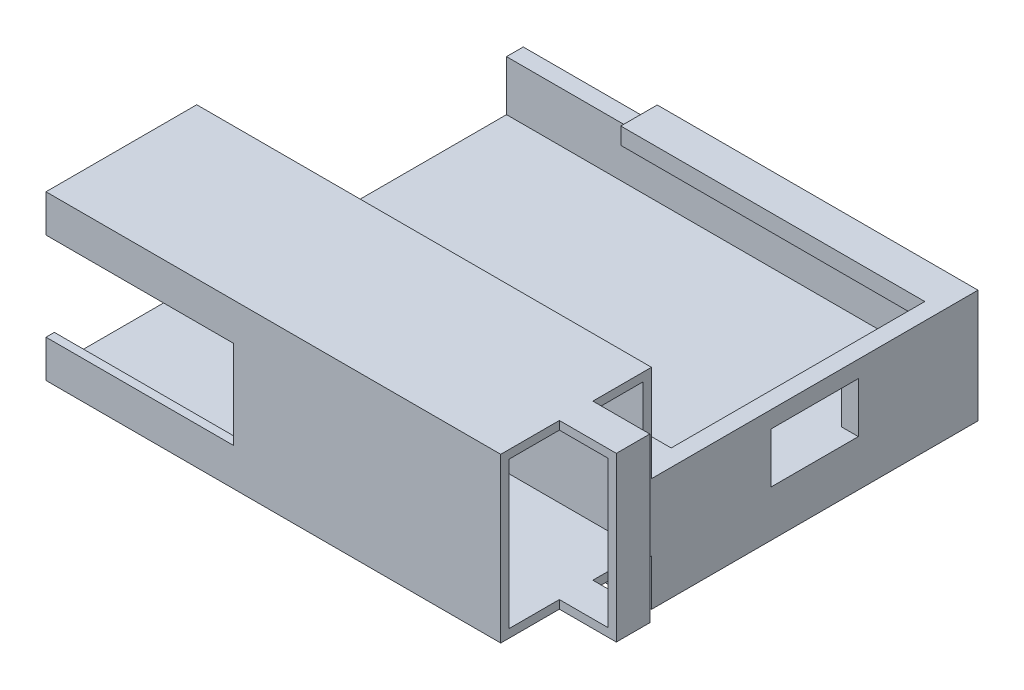
SolidWorks part; units mm, degrees
ref_plane "Front Plane" through (0, 0, 0) normal (0, 0, 1) x (1, 0, 0)
ref_plane "Top Plane" through (0, 0, 0) normal (0, 1, 0) x (1, 0, 0)
ref_plane "Right Plane" through (0, 0, 0) normal (1, 0, 0) x (0, 0, -1)
sketch "Sketch1" plane through (0, 0, 0) normal (1, 0, 0) x (0, 0, -1)
  line L0 (-3.4975, 0) -> (3.9817, 0) construction
  line L1 (-27.7749, 9.525) -> (-24.0411, 9.525)
  line L2 (0, 6.3447) -> (0, -3.1803) construction
  line L7 (-27.7749, 0) -> (27.7749, 0)
  line L8 (-27.7749, 0) -> (-27.7749, 9.525)
  line L9 (27.7749, 0) -> (27.7749, 9.525)
  line L10 (27.7749, 9.525) -> (24.0411, 9.525)
  line L11 (30.9499, 12.7) -> (24.0411, 12.7)
  line L12 (30.9499, -3.175) -> (30.9499, 12.7)
  line L14 (-30.9499, -3.175) -> (-30.9499, 12.7)
  line L15 (-30.9499, 12.7) -> (-24.0411, 12.7)
  line L16 (-24.0411, 12.7) -> (-24.0411, 9.525)
  line L17 (24.0411, 12.7) -> (24.0411, 9.525)
  line L18 (-30.9499, -8.763) -> (30.9499, -8.763)
  line L19 (-30.9499, -3.175) -> (-30.9499, -8.763)
  line L20 (30.9499, -3.175) -> (30.9499, -8.763)
  line L22 (-30.9499, -3.175) -> (30.9499, -3.175) construction
  point P3 (0, 0)
  dimension "D1" = 3.7338
  dimension "D2" = 3.175
  dimension "D4" = 9.525
extrude "Boss-Extrude1" add sketch "Sketch1" along normal blind 83.0326
sketch "Sketch2" plane through (83.0326, 0, 0) normal (1, 0, 0) x (0, 0, -1)
  line L0 (-30.9499, 12.7) -> (30.9499, 12.7)
  line L1 (30.9499, 12.7) -> (30.9499, -8.763)
  line L2 (30.9499, -8.763) -> (-30.9499, -8.763)
  line L3 (-30.9499, -8.763) -> (-30.9499, 12.7)
extrude "Boss-Extrude2" add sketch "Sketch2" along normal blind 3.175
sketch "Sketch3" plane through (0, 0, 30.9499) normal (0, 0, 1) x (1, 0, 0)
  line L0 (0, -4.8159) -> (86.2076, -4.8159) construction
  line L1 (0, 12.7) -> (0, -8.763) construction
  line L2 (86.2076, 12.7) -> (86.2076, -8.763) construction
  line L3 (43.1038, 12.7) -> (43.1038, -8.763) construction
  line L4 (36.7538, -7.3559) -> (11.3538, -7.3559)
  line L5 (36.7538, -7.3559) -> (36.7538, -2.2759)
  line L6 (36.7538, -2.2759) -> (11.3538, -2.2759)
  line L7 (11.3538, -7.3559) -> (11.3538, -2.2759)
  line L8 (36.7538, -7.3559) -> (11.3538, -2.2759) construction
  line L9 (36.7538, -2.2759) -> (11.3538, -7.3559) construction
  line L10 (86.2076, 12.7) -> (0, 12.7) construction
  line L11 (86.2076, -8.763) -> (0, -8.763) construction
  line L12 (74.8538, -7.3559) -> (74.8538, -2.2759)
  line L13 (49.4538, -2.2759) -> (74.8538, -2.2759)
  line L14 (49.4538, -7.3559) -> (49.4538, -2.2759)
  line L15 (49.4538, -7.3559) -> (74.8538, -7.3559)
  line L16 (24.0538, -2.2759) -> (24.0538, -7.3559) construction
  point P6 (24.0538, -4.8159)
  dimension "D1" = 25.4
  dimension "D2" = 19.05
  dimension "D3" = 5.08
extrude "Cut-Extrude1" cut sketch "Sketch3" against normal through all
fillet "Fillet1" radius 0.762 4 edges at (62.1538, -7.3559, -30.9499) (24.0538, -7.3559, -30.9499) (62.1538, -7.3559, 30.9499) (24.0538, -7.3559, 30.9499)
fillet "Fillet2" radius 0.762 6 edges at (11.3538, -5.1969, -30.9499) (24.0538, -2.2759, -30.9499) (36.7538, -5.1969, -30.9499) (49.4538, -5.1969, -30.9499) (62.1538, -2.2759, -30.9499) (74.8538, -5.1969, -30.9499)
fillet "Fillet3" radius 0.762 6 edges at (74.8538, -5.1969, 30.9499) (62.1538, -2.2759, 30.9499) (49.4538, -5.1969, 30.9499) (11.3538, -5.1969, 30.9499) (24.0538, -2.2759, 30.9499) (36.7538, -5.1969, 30.9499)
sketch "Sketch5" plane through (83.0326, 0, 0) normal (-1, 0, 0) x (0, 0, 1)
  line L0 (-27.7749, 4.7625) -> (27.7749, 4.7625) construction
  line L1 (-27.7749, 9.525) -> (-27.7749, 0) construction
  line L2 (27.7749, 0) -> (27.7749, 9.525) construction
  line L4 (8.265, 0) -> (-8.265, 0)
  line L5 (8.265, 0) -> (8.265, 9.525)
  line L6 (8.265, 9.525) -> (-8.265, 9.525)
  line L7 (-8.265, 0) -> (-8.265, 9.525)
  line L8 (8.265, 0) -> (-8.265, 9.525) construction
  line L9 (8.265, 9.525) -> (-8.265, 0) construction
  point P6 (0, 4.7625)
  dimension "D1" = 9.525
extrude "Cut-Extrude2" cut sketch "Sketch5" against normal through all
sketch "Sketch40" plane through (0, 0, 0) normal (-1, 0, 0) x (0, 0, 1)
  line L0 (27.7749, 0) -> (30.9499, 0) construction
  line L1 (-27.7749, 0) -> (27.7749, 0) construction
  line L2 (8.265, 0) -> (27.7749, 0) construction
  line L3 (30.9499, 12.7) -> (30.9499, -8.763) construction
sketch "Sketch41" plane through (0, 0, 30.9499) normal (0, 0, 1) x (1, 0, 0)
  line L0 (0, 0) -> (86.2076, 0)
  line L2 (0, 30.988) -> (86.2076, 30.988)
  line L3 (0, 30.988) -> (0, 0)
  line L4 (86.2076, 30.988) -> (86.2076, 0)
  dimension "D1" = 30.988
extrude "Boss-Extrude10" add sketch "Sketch41" along normal blind 1.5875
sketch "Sketch42" plane through (0, 0, 32.5374) normal (0, 0, 1) x (1, 0, 0)
  line L0 (0, 0) -> (86.2076, 0)
  line L1 (86.2076, 0) -> (86.2076, 1.5875)
  line L2 (86.2076, 0) -> (86.2076, 30.988) construction
  line L3 (86.2076, 1.5875) -> (0, 1.5875)
  line L4 (0, 30.988) -> (0, 0) construction
  line L5 (0, 1.5875) -> (0, 0)
  dimension "D1" = 1.5875
extrude "Boss-Extrude11" add sketch "Sketch42" along normal blind 25.4
sketch "Sketch43" plane through (0, 30.988, 0) normal (0, 1, 0) x (1, 0, 0)
  line L0 (0, -30.9499) -> (86.2076, -30.9499)
sketch "Sketch46" plane through (0, 0, 32.5374) normal (0, 0, 1) x (1, 0, 0)
  line L2 (0, 29.4005) -> (86.2076, 29.4005)
  line L3 (0, 29.4005) -> (86.2076, 29.4005)
  line L6 (0, 29.4005) -> (86.2076, 29.4005)
  dimension "D1" = 1.5875
sketch "Sketch47" plane through (0, 0, 32.5374) normal (0, 0, 1) x (1, 0, 0)
  line L0 (0, 30.988) -> (0, 29.4005)
  line L1 (0, 29.4005) -> (86.2076, 29.4005)
  line L2 (86.2076, 29.4005) -> (86.2076, 30.988)
  line L3 (86.2076, 30.988) -> (0, 30.988)
extrude "Boss-Extrude13" add sketch "Sketch47" along normal blind 25.4
sketch "Sketch48" plane through (0, 0, 57.9374) normal (0, 0, 1) x (1, 0, 0)
  line L0 (0, 30.988) -> (0, 0)
  line L1 (0, 0) -> (86.2076, 0)
  line L2 (86.2076, 0) -> (86.2076, 30.988)
  line L3 (86.2076, 30.988) -> (0, 30.988)
extrude "Boss-Extrude14" add sketch "Sketch48" along normal blind 1.5875
sketch "Sketch49" plane through (0, 0, 0) normal (-1, 0, 0) x (0, 0, 1)
  line L0 (59.5249, 15.494) -> (57.9374, 15.494) construction
  line L1 (59.5249, 30.988) -> (59.5249, 0) construction
  line L2 (57.9374, 29.4005) -> (57.9374, 1.5875) construction
  line L3 (59.5249, 23.876) -> (57.9374, 23.876)
  line L4 (59.5249, 7.112) -> (57.9374, 7.112)
  line L5 (57.9374, 23.876) -> (57.9374, 7.112)
  line L6 (59.5249, 7.112) -> (59.5249, 23.876)
  dimension "D1" = 8.382
  dimension "D2" = 8.382
extrude "Cut-Extrude5" cut sketch "Sketch49" against normal blind 35.56
sketch "Sketch50" plane through (86.2076, 0, 0) normal (1, 0, 0) x (0, 0, -1)
  line L0 (-59.5249, 15.494) -> (-30.9499, 15.494) construction
  line L1 (-59.5249, 0) -> (-59.5249, 30.988) construction
  line L2 (-30.9499, 12.7) -> (-30.9499, 30.988) construction
  line L3 (-45.2374, 30.988) -> (-45.2374, 29.4005) construction
  line L4 (-59.5249, 30.988) -> (-30.9499, 30.988) construction
  line L5 (-57.9374, 29.4005) -> (-32.5374, 29.4005) construction
  line L6 (-48.4124, 30.988) -> (-48.4124, 29.4005)
  line L7 (-57.9374, 1.5875) -> (-32.5374, 1.5875) construction
  line L8 (-45.2374, 1.5875) -> (-45.2374, 0) construction
  line L9 (-59.5249, 0) -> (-30.9499, 0) construction
  line L10 (-42.0624, 30.988) -> (-42.0624, 29.4005)
  line L11 (-48.4124, 1.5875) -> (-48.4124, 0)
  line L12 (-42.0624, 1.5875) -> (-42.0624, 0)
  line L13 (-48.4124, 30.988) -> (-42.0624, 30.988)
  line L14 (-42.0624, 29.4005) -> (-48.4124, 29.4005)
  line L15 (-48.4124, 0) -> (-42.0624, 0)
  line L16 (-42.0624, 1.5875) -> (-48.4124, 1.5875)
  dimension "D1" = 3.175
  dimension "D2" = 3.175
  dimension "D3" = 3.175
  dimension "D4" = 3.175
extrude "Boss-Extrude15" add sketch "Sketch50" along normal blind 9.2075
sketch "Sketch52" plane through (95.4151, 0, 0) normal (1, 0, 0) x (0, 0, -1)
  line L0 (-48.4124, 30.988) -> (-42.0624, 30.988)
  line L1 (-42.0624, 30.988) -> (-42.0624, 0)
  line L2 (-42.0624, 0) -> (-48.4124, 0)
  line L3 (-48.4124, 0) -> (-48.4124, 30.988)
extrude "Boss-Extrude17" add sketch "Sketch52" along normal blind 1.5875
sketch "Sketch53" plane through (0, 12.7, 0) normal (0, 1, 0) x (1, 0, 0)
  line L0 (0, 30.9499) -> (25.4, 30.9499)
  line L1 (86.2076, 30.9499) -> (0, 30.9499) construction
  line L2 (25.4, 30.9499) -> (25.4, -30.9499)
  line L3 (0, -30.9499) -> (86.2076, -30.9499) construction
  line L4 (25.4, -30.9499) -> (0, -30.9499)
  line L5 (0, -30.9499) -> (0, 30.9499)
  dimension "D1" = 25.4
extrude "Cut-Extrude6" cut sketch "Sketch53" against normal blind 3.175
